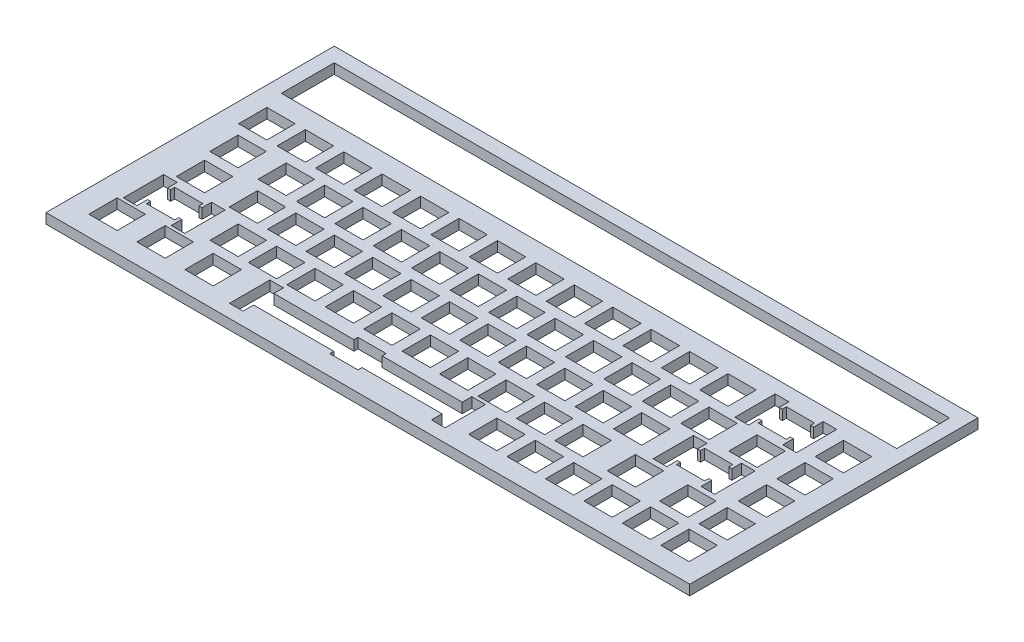
SolidWorks part; units mm, degrees
ref_plane "Front Plane" through (0, 0, 0) normal (0, 0, 1) x (1, 0, 0)
ref_plane "Top Plane" through (0, 0, 0) normal (0, 1, 0) x (1, 0, 0)
ref_plane "Right Plane" through (0, 0, 0) normal (1, 0, 0) x (0, 0, -1)
sketch "Sketch1" plane through (0, 0, 0) normal (0, 1, 0) x (1, 0, 0)
  line L2 (-75.7545, 37.9956) -> (-61.7545, 37.9956)
  line L3 (-94.8265, 37.9956) -> (-80.8265, 37.9956)
  line L4 (-94.8265, 37.9956) -> (-94.8265, 51.9956)
  line L5 (-94.8265, 51.9956) -> (-80.8265, 51.9956)
  line L6 (-80.8265, 37.9956) -> (-80.8265, 51.9956)
  line L7 (-75.7545, 37.9956) -> (-75.7545, 51.9956)
  line L8 (-75.7545, 51.9956) -> (-61.7545, 51.9956)
  line L9 (-61.7545, 37.9956) -> (-61.7545, 51.9956)
  line L10 (133.7495, 37.9956) -> (147.7495, 37.9956)
  line L11 (-37.6545, 37.9956) -> (-23.6545, 37.9956)
  line L12 (-56.7045, 37.9956) -> (-42.7045, 37.9956)
  line L13 (-56.7045, 37.9956) -> (-56.7045, 51.9956)
  line L14 (-56.7045, 51.9956) -> (-42.7045, 51.9956)
  line L15 (-42.7045, 37.9956) -> (-42.7045, 51.9956)
  line L16 (-37.6545, 37.9956) -> (-37.6545, 51.9956)
  line L17 (-37.6545, 51.9956) -> (-23.6545, 51.9956)
  line L18 (-23.6545, 37.9956) -> (-23.6545, 51.9956)
  line L19 (133.7495, 37.9956) -> (133.7495, 51.9956)
  line L20 (133.7495, 51.9956) -> (147.7495, 51.9956)
  line L21 (0.4455, 37.9956) -> (14.4455, 37.9956)
  line L22 (-18.6045, 37.9956) -> (-4.6045, 37.9956)
  line L23 (-18.6045, 37.9956) -> (-18.6045, 51.9956)
  line L24 (-18.6045, 51.9956) -> (-4.6045, 51.9956)
  line L25 (-4.6045, 37.9956) -> (-4.6045, 51.9956)
  line L26 (0.4455, 37.9956) -> (0.4455, 51.9956)
  line L27 (0.4455, 51.9956) -> (14.4455, 51.9956)
  line L28 (14.4455, 37.9956) -> (14.4455, 51.9956)
  line L29 (147.7495, 37.9956) -> (147.7495, 51.9956)
  line L30 (38.5455, 37.9956) -> (52.5455, 37.9956)
  line L31 (19.4955, 37.9956) -> (33.4955, 37.9956)
  line L32 (19.4955, 37.9956) -> (19.4955, 51.9956)
  line L33 (19.4955, 51.9956) -> (33.4955, 51.9956)
  line L34 (33.4955, 37.9956) -> (33.4955, 51.9956)
  line L35 (38.5455, 37.9956) -> (38.5455, 51.9956)
  line L36 (38.5455, 51.9956) -> (52.5455, 51.9956)
  line L37 (52.5455, 37.9956) -> (52.5455, 51.9956)
  line L38 (147.7495, 44.9956) -> (154.1495, 44.9956) construction
  line L39 (167.1835, 18.9456) -> (181.1835, 18.9456)
  line L40 (167.1835, 18.9456) -> (167.1835, 32.9456)
  line L41 (76.6455, 37.9956) -> (90.6455, 37.9956)
  line L42 (57.5955, 37.9956) -> (71.5955, 37.9956)
  line L43 (57.5955, 37.9956) -> (57.5955, 51.9956)
  line L44 (57.5955, 51.9956) -> (71.5955, 51.9956)
  line L45 (71.5955, 37.9956) -> (71.5955, 51.9956)
  line L46 (76.6455, 37.9956) -> (76.6455, 51.9956)
  line L47 (76.6455, 51.9956) -> (90.6455, 51.9956)
  line L48 (90.6455, 37.9956) -> (90.6455, 51.9956)
  line L49 (167.1835, 32.9456) -> (181.1835, 32.9456)
  line L50 (114.7225, 37.9956) -> (128.7225, 37.9956)
  line L51 (95.6955, 37.9956) -> (109.6955, 37.9956)
  line L52 (95.6955, 37.9956) -> (95.6955, 51.9956)
  line L53 (95.6955, 51.9956) -> (109.6955, 51.9956)
  line L54 (109.6955, 37.9956) -> (109.6955, 51.9956)
  line L55 (114.7225, 37.9956) -> (114.7225, 51.9956)
  line L56 (114.7225, 51.9956) -> (128.7225, 51.9956)
  line L57 (128.7225, 37.9956) -> (128.7225, 51.9956)
  line L58 (181.1835, 18.9456) -> (181.1835, 32.9456)
  line L59 (157.3735, 25.9456) -> (167.1835, 25.9456) construction
  line L73 (162.3995, 52.2456) -> (176.3995, 52.2456)
  line L75 (176.3995, 38.2456) -> (162.3995, 38.2456)
  line L77 (176.3995, 52.2456) -> (176.3995, 50.2456)
  line L78 (176.3995, 50.2456) -> (177.8995, 50.2456)
  line L79 (177.8995, 50.2456) -> (177.8995, 54.9956)
  line L80 (177.8995, 54.9956) -> (184.6495, 54.9956)
  line L81 (184.6495, 54.9956) -> (184.6495, 34.9956)
  line L82 (184.6495, 34.9956) -> (177.8995, 34.9956)
  line L83 (177.8995, 34.9956) -> (177.8995, 40.2456)
  line L84 (177.8995, 40.2456) -> (176.3995, 40.2456)
  line L85 (176.3995, 40.2456) -> (176.3995, 38.2456)
  line L86 (162.3995, 52.2456) -> (162.3995, 50.2456)
  line L87 (160.8995, 54.9956) -> (160.8995, 50.2456)
  line L88 (160.8995, 50.2456) -> (162.3995, 50.2456)
  line L89 (160.8995, 54.9956) -> (154.1495, 54.9956)
  line L90 (154.1495, 54.9956) -> (154.1495, 34.9956)
  line L91 (154.1495, 34.9956) -> (160.8995, 34.9956)
  line L92 (160.8995, 34.9956) -> (160.8995, 40.2456)
  line L93 (160.8995, 40.2456) -> (162.3995, 40.2456)
  line L94 (162.3995, 40.2456) -> (162.3995, 38.2456)
  line L116 (-47.1265, 18.9456) -> (-33.1265, 18.9456)
  line L117 (-66.1765, 18.9456) -> (-52.1765, 18.9456)
  line L118 (-66.1765, 18.9456) -> (-66.1765, 32.9456)
  line L119 (-66.1765, 32.9456) -> (-52.1765, 32.9456)
  line L120 (-52.1765, 18.9456) -> (-52.1765, 32.9456)
  line L121 (-47.1265, 18.9456) -> (-47.1265, 32.9456)
  line L122 (-47.1265, 32.9456) -> (-33.1265, 32.9456)
  line L123 (-33.1265, 18.9456) -> (-33.1265, 32.9456)
  line L125 (-9.0515, 18.9456) -> (4.9485, 18.9456)
  line L126 (-28.0765, 18.9456) -> (-14.0765, 18.9456)
  line L127 (-28.0765, 18.9456) -> (-28.0765, 32.9456)
  line L128 (-28.0765, 32.9456) -> (-14.0765, 32.9456)
  line L129 (-14.0765, 18.9456) -> (-14.0765, 32.9456)
  line L130 (-9.0515, 18.9456) -> (-9.0515, 32.9456)
  line L131 (-9.0515, 32.9456) -> (4.9485, 32.9456)
  line L132 (4.9485, 18.9456) -> (4.9485, 32.9456)
  line L135 (29.0735, 18.9456) -> (43.0735, 18.9456)
  line L136 (9.9485, 18.9456) -> (23.9485, 18.9456)
  line L137 (9.9485, 18.9456) -> (9.9485, 32.9456)
  line L138 (9.9485, 32.9456) -> (23.9485, 32.9456)
  line L139 (23.9485, 18.9456) -> (23.9485, 32.9456)
  line L140 (29.0735, 18.9456) -> (29.0735, 32.9456)
  line L141 (29.0735, 32.9456) -> (43.0735, 32.9456)
  line L142 (43.0735, 18.9456) -> (43.0735, 32.9456)
  line L144 (67.1485, 18.9456) -> (81.1485, 18.9456)
  line L145 (48.1235, 18.9456) -> (62.1235, 18.9456)
  line L146 (48.1235, 18.9456) -> (48.1235, 32.9456)
  line L147 (48.1235, 32.9456) -> (62.1235, 32.9456)
  line L148 (62.1235, 18.9456) -> (62.1235, 32.9456)
  line L149 (67.1485, 18.9456) -> (67.1485, 32.9456)
  line L150 (67.1485, 32.9456) -> (81.1485, 32.9456)
  line L151 (81.1485, 18.9456) -> (81.1485, 32.9456)
  line L152 (159.9865, 14.1456) -> (173.9865, 14.1456)
  line L153 (-42.3635, -0.1044) -> (-28.3635, -0.1044)
  line L154 (-61.4135, -0.1044) -> (-47.4135, -0.1044)
  line L155 (105.2735, 18.9456) -> (119.2735, 18.9456)
  line L156 (86.2235, 18.9456) -> (100.2235, 18.9456)
  line L157 (86.2235, 18.9456) -> (86.2235, 32.9456)
  line L158 (86.2235, 32.9456) -> (100.2235, 32.9456)
  line L159 (100.2235, 18.9456) -> (100.2235, 32.9456)
  line L160 (105.2735, 18.9456) -> (105.2735, 32.9456)
  line L161 (105.2735, 32.9456) -> (119.2735, 32.9456)
  line L162 (119.2735, 18.9456) -> (119.2735, 32.9456)
  line L163 (-61.4135, -0.1044) -> (-61.4135, 13.8956)
  line L172 (-94.8265, 37.9956) -> (-94.8265, 32.9456) construction
  line L173 (-61.4135, 13.8956) -> (-47.4135, 13.8956)
  line L174 (-47.4135, -0.1044) -> (-47.4135, 13.8956)
  line L175 (-90.0635, 18.9456) -> (-76.0635, 18.9456)
  line L176 (-90.0635, 18.9456) -> (-90.0635, 32.9456)
  line L177 (-90.0635, 32.9456) -> (-76.0635, 32.9456)
  line L178 (-76.0635, 18.9456) -> (-76.0635, 32.9456)
  line L179 (-94.8265, 32.9456) -> (-90.0635, 32.9456) construction
  line L180 (124.3235, 18.9456) -> (138.3235, 18.9456)
  line L185 (124.3235, 18.9456) -> (124.3235, 32.9456)
  line L186 (124.3235, 32.9456) -> (138.3235, 32.9456)
  line L187 (138.3235, 18.9456) -> (138.3235, 32.9456)
  line L188 (-42.3635, -0.1044) -> (-42.3635, 13.8956)
  line L189 (143.3735, 18.9456) -> (157.3735, 18.9456)
  line L190 (143.3735, 18.9456) -> (143.3735, 32.9456)
  line L191 (143.3735, 32.9456) -> (157.3735, 32.9456)
  line L192 (157.3735, 18.9456) -> (157.3735, 32.9456)
  line L193 (-42.3635, 13.8956) -> (-28.3635, 13.8956)
  line L194 (-28.3635, -0.1044) -> (-28.3635, 13.8956)
  line L195 (-4.2635, -0.1044) -> (9.7365, -0.1044)
  line L196 (-23.3135, -0.1044) -> (-9.3135, -0.1044)
  line L197 (-23.3135, -0.1044) -> (-23.3135, 13.8956)
  line L198 (-23.3135, 13.8956) -> (-9.3135, 13.8956)
  line L199 (-9.3135, -0.1044) -> (-9.3135, 13.8956)
  line L200 (-4.2635, -0.1044) -> (-4.2635, 13.8956)
  line L201 (-4.2635, 13.8956) -> (9.7365, 13.8956)
  line L202 (9.7365, -0.1044) -> (9.7365, 13.8956)
  line L203 (33.8365, -0.1044) -> (47.8365, -0.1044)
  line L204 (14.7865, -0.1044) -> (28.7865, -0.1044)
  line L205 (14.7865, -0.1044) -> (14.7865, 13.8956)
  line L206 (14.7865, 13.8956) -> (28.7865, 13.8956)
  line L207 (28.7865, -0.1044) -> (28.7865, 13.8956)
  line L208 (33.8365, -0.1044) -> (33.8365, 13.8956)
  line L209 (33.8365, 13.8956) -> (47.8365, 13.8956)
  line L210 (47.8365, -0.1044) -> (47.8365, 13.8956)
  line L211 (71.9365, -0.1044) -> (85.9365, -0.1044)
  line L212 (52.8865, -0.1044) -> (66.8865, -0.1044)
  line L213 (52.8865, -0.1044) -> (52.8865, 13.8956)
  line L214 (52.8865, 13.8956) -> (66.8865, 13.8956)
  line L215 (66.8865, -0.1044) -> (66.8865, 13.8956)
  line L216 (71.9365, -0.1044) -> (71.9365, 13.8956)
  line L217 (71.9365, 13.8956) -> (85.9365, 13.8956)
  line L218 (85.9365, -0.1044) -> (85.9365, 13.8956)
  line L219 (110.0365, -0.1044) -> (124.0365, -0.1044)
  line L220 (90.9865, -0.1044) -> (104.9865, -0.1044)
  line L221 (90.9865, -0.1044) -> (90.9865, 13.8956)
  line L222 (90.9865, 13.8956) -> (104.9865, 13.8956)
  line L223 (104.9865, -0.1044) -> (104.9865, 13.8956)
  line L224 (110.0365, -0.1044) -> (110.0365, 13.8956)
  line L225 (110.0365, 13.8956) -> (124.0365, 13.8956)
  line L226 (124.0365, -0.1044) -> (124.0365, 13.8956)
  line L227 (-87.6075, -0.1044) -> (-73.6075, -0.1044)
  line L228 (-87.6075, -0.1044) -> (-87.6075, 13.8956)
  line L229 (-87.6075, 13.8956) -> (-73.6075, 13.8956)
  line L230 (-73.6075, -0.1044) -> (-73.6075, 13.8956)
  line L231 (-90.0635, 18.9456) -> (-90.0635, 13.8956) construction
  line L232 (129.0865, -0.1044) -> (143.0865, -0.1044)
  line L233 (129.0865, -0.1044) -> (129.0865, 13.8956)
  line L234 (129.0865, 13.8956) -> (143.0865, 13.8956)
  line L235 (143.0865, -0.1044) -> (143.0865, 13.8956)
  line L240 (-90.0635, 13.8956) -> (-87.6075, 13.8956) construction
  line L241 (173.9865, 0.1456) -> (159.9865, 0.1456)
  line L242 (173.9865, 14.1456) -> (173.9865, 12.1456)
  line L243 (173.9865, 12.1456) -> (175.4865, 12.1456)
  line L244 (175.4865, 12.1456) -> (175.4865, 16.8956)
  line L245 (175.4865, 16.8956) -> (182.2365, 16.8956)
  line L246 (182.2365, 16.8956) -> (182.2365, -3.1044)
  line L247 (182.2365, -3.1044) -> (175.4865, -3.1044)
  line L248 (175.4865, -3.1044) -> (175.4865, 2.1456)
  line L249 (175.4865, 2.1456) -> (173.9865, 2.1456)
  line L250 (173.9865, 2.1456) -> (173.9865, 0.1456)
  line L251 (159.9865, 14.1456) -> (159.9865, 12.1456)
  line L252 (158.4865, 16.8956) -> (158.4865, 12.1456)
  line L253 (158.4865, 12.1456) -> (159.9865, 12.1456)
  line L254 (158.4865, 16.8956) -> (151.7365, 16.8956)
  line L255 (151.7365, 16.8956) -> (151.7365, -3.1044)
  line L256 (151.7365, -3.1044) -> (158.4865, -3.1044)
  line L257 (158.4865, -3.1044) -> (158.4865, 2.1456)
  line L258 (158.4865, 2.1456) -> (159.9865, 2.1456)
  line L259 (159.9865, 2.1456) -> (159.9865, 0.1456)
  line L260 (143.0865, 12.1456) -> (151.7365, 12.1456) construction
  line L262 (-32.8385, -19.1544) -> (-18.8385, -19.1544)
  line L263 (-51.8885, -19.1544) -> (-37.8885, -19.1544)
  line L264 (-51.8885, -19.1544) -> (-51.8885, -5.1544)
  line L265 (-51.8885, -5.1544) -> (-37.8885, -5.1544)
  line L266 (-37.8885, -19.1544) -> (-37.8885, -5.1544)
  line L267 (-32.8385, -19.1544) -> (-32.8385, -5.1544)
  line L268 (-32.8385, -5.1544) -> (-18.8385, -5.1544)
  line L269 (-18.8385, -19.1544) -> (-18.8385, -5.1544)
  line L270 (5.2615, -19.1544) -> (19.2615, -19.1544)
  line L271 (-13.7885, -19.1544) -> (0.2115, -19.1544)
  line L272 (-13.7885, -19.1544) -> (-13.7885, -5.1544)
  line L273 (-13.7885, -5.1544) -> (0.2115, -5.1544)
  line L274 (0.2115, -19.1544) -> (0.2115, -5.1544)
  line L275 (5.2615, -19.1544) -> (5.2615, -5.1544)
  line L276 (5.2615, -5.1544) -> (19.2615, -5.1544)
  line L277 (19.2615, -19.1544) -> (19.2615, -5.1544)
  line L278 (43.3615, -19.1544) -> (57.3615, -19.1544)
  line L279 (24.3115, -19.1544) -> (38.3115, -19.1544)
  line L280 (24.3115, -19.1544) -> (24.3115, -5.1544)
  line L281 (24.3115, -5.1544) -> (38.3115, -5.1544)
  line L282 (38.3115, -19.1544) -> (38.3115, -5.1544)
  line L283 (43.3615, -19.1544) -> (43.3615, -5.1544)
  line L284 (43.3615, -5.1544) -> (57.3615, -5.1544)
  line L285 (57.3615, -19.1544) -> (57.3615, -5.1544)
  line L286 (81.4615, -19.6544) -> (95.4615, -19.6544)
  line L287 (62.4115, -19.6544) -> (76.4115, -19.6544)
  line L288 (62.4115, -19.6544) -> (62.4115, -5.6544)
  line L289 (62.4115, -5.6544) -> (76.4115, -5.6544)
  line L290 (76.4115, -19.6544) -> (76.4115, -5.6544)
  line L291 (81.4615, -19.6544) -> (81.4615, -5.6544)
  line L292 (81.4615, -5.6544) -> (95.4615, -5.6544)
  line L293 (95.4615, -19.6544) -> (95.4615, -5.6544)
  line L294 (119.5615, -19.6544) -> (133.5615, -19.6544)
  line L295 (100.5115, -19.6544) -> (114.5115, -19.6544)
  line L296 (100.5115, -19.6544) -> (100.5115, -5.6544)
  line L297 (100.5115, -5.6544) -> (114.5115, -5.6544)
  line L298 (114.5115, -19.6544) -> (114.5115, -5.6544)
  line L299 (119.5615, -19.6544) -> (119.5615, -5.6544)
  line L300 (119.5615, -5.6544) -> (133.5615, -5.6544)
  line L301 (133.5615, -19.6544) -> (133.5615, -5.6544)
  line L306 (-83.3445, -5.1544) -> (-69.3445, -5.1544)
  line L307 (145.5235, -19.6544) -> (159.5235, -19.6544)
  line L308 (145.5235, -19.6544) -> (145.5235, -5.6544)
  line L309 (145.5235, -5.6544) -> (159.5235, -5.6544)
  line L310 (159.5235, -19.6544) -> (159.5235, -5.6544)
  line L311 (-69.3445, -19.1544) -> (-83.3445, -19.1544)
  line L331 (171.4855, -19.6544) -> (185.4855, -19.6544)
  line L332 (171.4855, -19.6544) -> (171.4855, -5.6544)
  line L333 (171.4855, -5.6544) -> (185.4855, -5.6544)
  line L334 (185.4855, -19.6544) -> (185.4855, -5.6544)
  line L335 (159.5235, -12.6544) -> (171.4855, -12.6544) construction
  line L336 (-61.4135, -0.1044) -> (-61.4135, -5.1544) construction
  line L337 (-61.4135, -5.1544) -> (-51.8885, -5.1544) construction
  line L339 (-97.2765, 61.6456) -> (207.7235, 61.6456)
  line L340 (190.9955, 18.9456) -> (204.9955, 18.9456)
  line L341 (190.9955, 18.9456) -> (190.9955, 32.9456)
  line L342 (190.9955, 32.9456) -> (204.9955, 32.9456)
  line L343 (204.9955, 18.9456) -> (204.9955, 32.9456)
  line L344 (181.1835, 25.9456) -> (190.9955, 25.9456) construction
  line L345 (190.9745, 37.9956) -> (204.9745, 37.9956)
  line L346 (190.9745, 37.9956) -> (190.9745, 51.9956)
  line L347 (190.9745, 51.9956) -> (204.9745, 51.9956)
  line L348 (204.9745, 37.9956) -> (204.9745, 51.9956)
  line L349 (184.6495, 44.9956) -> (190.9745, 44.9956) construction
  line L350 (190.9425, -0.1044) -> (204.9425, -0.1044)
  line L351 (190.9425, -0.1044) -> (190.9425, 13.8956)
  line L352 (190.9425, 13.8956) -> (204.9425, 13.8956)
  line L353 (204.9425, -0.1044) -> (204.9425, 13.8956)
  line L354 (182.2365, 6.8956) -> (190.9425, 6.8956) construction
  line L355 (190.9855, -19.6544) -> (204.9855, -19.6544)
  line L356 (190.9855, -19.6544) -> (190.9855, -5.6544)
  line L357 (190.9855, -5.6544) -> (204.9855, -5.6544)
  line L358 (204.9855, -19.6544) -> (204.9855, -5.6544)
  line L359 (185.4855, -12.6544) -> (190.9855, -12.6544) construction
  line L360 (-69.3445, -5.1544) -> (-69.3445, -7.1544)
  line L361 (-69.3445, -7.1544) -> (-67.8445, -7.1544)
  line L362 (-67.8445, -7.1544) -> (-67.8445, -2.4044)
  line L363 (-67.8445, -2.4044) -> (-61.0945, -2.4044)
  line L364 (-61.0945, -2.4044) -> (-61.0945, -22.4044)
  line L365 (-61.0945, -22.4044) -> (-67.8445, -22.4044)
  line L366 (-67.8445, -22.4044) -> (-67.8445, -17.1544)
  line L367 (-67.8445, -17.1544) -> (-69.3445, -17.1544)
  line L368 (-69.3445, -17.1544) -> (-69.3445, -19.1544)
  line L369 (-83.3445, -5.1544) -> (-83.3445, -7.1544)
  line L370 (-84.8445, -2.4044) -> (-84.8445, -7.1544)
  line L371 (-84.8445, -7.1544) -> (-83.3445, -7.1544)
  line L372 (-84.8445, -2.4044) -> (-91.5945, -2.4044)
  line L373 (-91.5945, -2.4044) -> (-91.5945, -22.4044)
  line L374 (-91.5945, -22.4044) -> (-84.8445, -22.4044)
  line L375 (-84.8445, -22.4044) -> (-84.8445, -17.1544)
  line L376 (-84.8445, -17.1544) -> (-83.3445, -17.1544)
  line L377 (-83.3445, -17.1544) -> (-83.3445, -19.1544)
  line L378 (-93.0945, -37.9544) -> (-79.0945, -37.9544)
  line L379 (-93.0945, -37.9544) -> (-93.0945, -23.9544)
  line L380 (-93.0945, -23.9544) -> (-79.0945, -23.9544)
  line L381 (-79.0945, -37.9544) -> (-79.0945, -23.9544)
  line L382 (-69.2945, -37.9544) -> (-55.2945, -37.9544)
  line L383 (-69.2945, -37.9544) -> (-69.2945, -23.9544)
  line L384 (-69.2945, -23.9544) -> (-55.2945, -23.9544)
  line L385 (-55.2945, -37.9544) -> (-55.2945, -23.9544)
  line L390 (-45.4945, -37.9544) -> (-31.4945, -37.9544)
  line L391 (-45.4945, -37.9544) -> (-45.4945, -23.9544)
  line L392 (-45.4945, -23.9544) -> (-31.4945, -23.9544)
  line L393 (-31.4945, -37.9544) -> (-31.4945, -23.9544)
  line L394 (-55.2945, -23.9544) -> (-45.4945, -23.9544) construction
  line L395 (26.4395, -24.1144) -> (40.4395, -24.1144)
  line L396 (40.4395, -38.1144) -> (26.4395, -38.1144)
  line L397 (40.4395, -24.1144) -> (40.4395, -26.1144)
  line L398 (40.4395, -26.1144) -> (80.1235, -26.1144)
  line L399 (80.1235, -26.1144) -> (80.1235, -21.3644)
  line L400 (80.1235, -21.3644) -> (86.8735, -21.3644)
  line L401 (86.8735, -21.3644) -> (86.8735, -41.3644)
  line L402 (86.8735, -41.3644) -> (80.1235, -41.3644)
  line L403 (80.1235, -41.3644) -> (80.1235, -36.1144)
  line L404 (80.1235, -36.1144) -> (40.4395, -36.1144)
  line L405 (40.4395, -36.1144) -> (40.4395, -38.1144)
  line L406 (26.4395, -24.1144) -> (26.4395, -26.1144)
  line L407 (-13.2445, -21.3644) -> (-13.2445, -26.1144)
  line L408 (-13.2445, -26.1144) -> (26.4395, -26.1144)
  line L409 (-13.2445, -21.3644) -> (-19.9945, -21.3644)
  line L410 (-19.9945, -21.3644) -> (-19.9945, -41.3644)
  line L411 (-19.9945, -41.3644) -> (-13.2445, -41.3644)
  line L412 (-13.2445, -41.3644) -> (-13.2445, -36.1144)
  line L413 (-13.2445, -36.1144) -> (26.4395, -36.1144)
  line L414 (26.4395, -36.1144) -> (26.4395, -38.1144)
  line L415 (95.5435, -38.3644) -> (109.5435, -38.3644)
  line L416 (95.5435, -38.3644) -> (95.5435, -24.3644)
  line L417 (95.5435, -24.3644) -> (109.5435, -24.3644)
  line L418 (109.5435, -38.3644) -> (109.5435, -24.3644)
  line L419 (86.8735, -31.3644) -> (95.5435, -31.3644) construction
  line L420 (114.5935, -38.3644) -> (128.5935, -38.3644)
  line L421 (114.5935, -38.3644) -> (114.5935, -24.3644)
  line L422 (114.5935, -24.3644) -> (128.5935, -24.3644)
  line L423 (128.5935, -38.3644) -> (128.5935, -24.3644)
  line L424 (114.5935, -31.3644) -> (109.5435, -31.3644) construction
  line L425 (133.6435, -38.3644) -> (147.6435, -38.3644)
  line L426 (133.6435, -38.3644) -> (133.6435, -24.3644)
  line L427 (133.6435, -24.3644) -> (147.6435, -24.3644)
  line L428 (147.6435, -38.3644) -> (147.6435, -24.3644)
  line L429 (152.6935, -38.3644) -> (166.6935, -38.3644)
  line L430 (152.6935, -38.3644) -> (152.6935, -24.3644)
  line L431 (152.6935, -24.3644) -> (166.6935, -24.3644)
  line L432 (166.6935, -38.3644) -> (166.6935, -24.3644)
  line L433 (171.7435, -38.3644) -> (185.7435, -38.3644)
  line L434 (171.7435, -38.3644) -> (171.7435, -24.3644)
  line L435 (171.7435, -24.3644) -> (185.7435, -24.3644)
  line L436 (185.7435, -38.3644) -> (185.7435, -24.3644)
  line L437 (190.7935, -38.3644) -> (204.7935, -38.3644)
  line L438 (190.7935, -38.3644) -> (190.7935, -24.3644)
  line L439 (190.7935, -24.3644) -> (204.7935, -24.3644)
  line L440 (204.7935, -38.3644) -> (204.7935, -24.3644)
  line L441 (-97.2765, 61.6456) -> (-97.2765, 87.8456)
  line L442 (-97.2765, 87.8456) -> (207.7235, 87.8456)
  line L443 (207.7235, 61.6456) -> (207.7235, 87.8456)
  line L444 (-104.4215, 94.9896) -> (214.6585, 94.9896)
  line L445 (-104.4215, 94.9896) -> (-104.4215, -47.8854)
  line L446 (-104.4215, -47.8854) -> (214.6585, -47.8854)
  line L447 (214.6585, 94.9896) -> (214.6585, -47.8854)
  point P115 (128.7225, 44.9956)
  point P116 (154.1495, 44.9956)
  dimension "D1" = 14
  dimension "D2" = 20
  dimension "D3" = 4.75
  dimension "D4" = 6.75
  dimension "D5" = 1.5
  dimension "D6" = 2
  dimension "D13" = 14
  dimension "D14" = 14
  dimension "D15" = 5.072
  dimension "D16" = 14
  dimension "D17" = 5.05
  dimension "D18" = 5.05
  dimension "D19" = 14
  dimension "D20" = 4.763
  dimension "D21" = 5.05
  dimension "D22" = 9.887
  dimension "D23" = 26.2
  dimension "D24" = 14
  dimension "D25" = 14
  dimension "D26" = 5.05
  dimension "D27" = 5.05
  dimension "D28" = 5.05
  dimension "D29" = 5.05
  dimension "D30" = 5.05
  dimension "D31" = 5.05
  dimension "D32" = 5.05
  dimension "D33" = 5.05
  dimension "D34" = 5.05
  dimension "D35" = 5.027
  dimension "D36" = 5.05
  dimension "D37" = 5.05
  dimension "D38" = 5.025
  dimension "D39" = 5
  dimension "D40" = 5.125
  dimension "D41" = 5.05
  dimension "D42" = 5.025
  dimension "D43" = 5.075
  dimension "D44" = 5.05
  dimension "D45" = 5.05
  dimension "D46" = 5.027
  dimension "D47" = 14.65
  dimension "D48" = 14
  dimension "D49" = 9.81
  dimension "D50" = 12.194
  dimension "D51" = 5.05
  dimension "D52" = 5.05
  dimension "D53" = 5.05
  dimension "D54" = 5.05
  dimension "D55" = 5.05
  dimension "D56" = 5.05
  dimension "D57" = 5.05
  dimension "D58" = 5.05
  dimension "D59" = 5.05
  dimension "D60" = 5.05
  dimension "D61" = 14
  dimension "D62" = 20
  dimension "D63" = 5.05
  dimension "D64" = 2.456
  dimension "D65" = 4.75
  dimension "D66" = 6.75
  dimension "D67" = 1.5
  dimension "D68" = 2
  dimension "D69" = 16.9
  dimension "D70" = 14
  dimension "D71" = 5.05
  dimension "D72" = 5.05
  dimension "D73" = 5.05
  dimension "D74" = 5.05
  dimension "D75" = 5.05
  dimension "D76" = 5.05
  dimension "D77" = 5.05
  dimension "D78" = 5.05
  dimension "D79" = 5.05
  dimension "D80" = 11.962
  dimension "D81" = 20
  dimension "D82" = 14
  dimension "D83" = 11.962
  dimension "D84" = 14
  dimension "D85" = 14
  dimension "D86" = 9.812
  dimension "D87" = 14
  dimension "D88" = 14.575
  dimension "D89" = 4.75
  dimension "D90" = 14
  dimension "D91" = 6.75
  dimension "D92" = 14
  dimension "D93" = 16.956
  dimension "D94" = 14
  dimension "D95" = 5.5
  dimension "D96" = 5.05
  dimension "D97" = 5.05
  dimension "D98" = 9.525
  dimension "D99" = 1.5
  dimension "D100" = 2
  dimension "D101" = 5.05
  dimension "D102" = 9.206
  dimension "D103" = 5.05
  dimension "D104" = 14
  dimension "D105" = 14
  dimension "D106" = 14
  dimension "D107" = 14
  dimension "D108" = 1.5
  dimension "D109" = 9.8
  dimension "D110" = 5.05
  dimension "D111" = 9.8
  dimension "D112" = 5.05
  dimension "D113" = 5.05
  dimension "D114" = 14
  dimension "D115" = 14
  dimension "D116" = 20
  dimension "D117" = 4.75
  dimension "D118" = 6.75
  dimension "D119" = 39.684
  dimension "D120" = 2
  dimension "D121" = 5.05
  dimension "D122" = 11.5
  dimension "D123" = 14
  dimension "D124" = 8.67
  dimension "D125" = 5.25
  dimension "D126" = 14
  dimension "D127" = 5.05
  dimension "D128" = 14
  dimension "D129" = 14
  dimension "D130" = 14
  dimension "D131" = 14
  dimension "D132" = 5.05
  dimension "D133" = 5.05
  dimension "D134" = 5.05
  dimension "D135" = 5.05
  dimension "D136" = 4.8
  dimension "D137" = 5.25
  dimension "D138" = 5.25
  dimension "D139" = 5.25
  dimension "D140" = 305
  dimension "D141" = 9.65
  dimension "D142" = 142.875
  dimension "D143" = 319.08
  dimension "D144" = 7.144
  dimension "D145" = 7.145
  dimension "D146" = 2.45
extrude "Boss-Extrude1" add sketch "Sketch1" against normal blind 5
